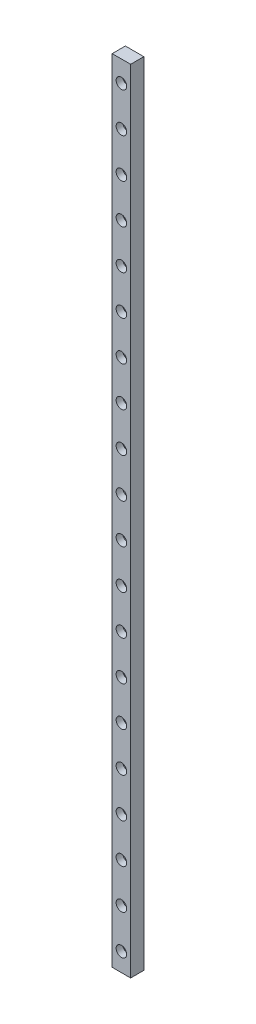
SolidWorks part; units mm, degrees
ref_plane "Front Plane" through (0, 0, 0) normal (0, 0, 1) x (1, 0, 0)
ref_plane "Top Plane" through (0, 0, 0) normal (0, 1, 0) x (1, 0, 0)
ref_plane "Right Plane" through (0, 0, 0) normal (1, 0, 0) x (0, 0, -1)
sketch "草图1" plane through (0, 0, 0) normal (0, 1, 0) x (1, 0, 0)
  line L1 (-3.5, 2.5) -> (3.5, 2.5)
  line L2 (-3.5, 2.5) -> (-3.5, -2.5)
  line L3 (-3.5, -2.5) -> (3.5, -2.5)
  line L4 (3.5, 2.5) -> (3.5, -2.5)
  line L5 (-3.5, 2.5) -> (3.5, -2.5) construction
  line L6 (-3.5, -2.5) -> (3.5, 2.5) construction
  point P0 (0, 0)
  dimension "D1" = 5
  dimension "D2" = 7
extrude "凸台-拉伸1" add sketch "草图1" along normal blind 300
sketch "草图2" plane through (0, 0, 2.5) normal (0, 0, 1) x (1, 0, 0)
  line L0 (-3.5, 0) -> (3.5, 0) construction
  circle A0 centre (0, 7) radius 1.25
  circle A1 centre (0, 22) radius 1.25
  circle A2 centre (0, 37) radius 1.25
  circle A3 centre (0, 52) radius 1.25
  circle A4 centre (0, 67) radius 1.25
  circle A5 centre (0, 82) radius 1.25
  circle A6 centre (0, 97) radius 1.25
  circle A7 centre (0, 112) radius 1.25
  circle A8 centre (0, 127) radius 1.25
  circle A9 centre (0, 142) radius 1.25
  circle A10 centre (0, 157) radius 1.25
  circle A11 centre (0, 172) radius 1.25
  circle A12 centre (0, 187) radius 1.25
  circle A13 centre (0, 202) radius 1.25
  circle A14 centre (0, 217) radius 1.25
  circle A15 centre (0, 232) radius 1.25
  circle A16 centre (0, 247) radius 1.25
  circle A17 centre (0, 262) radius 1.25
  circle A18 centre (0, 277) radius 1.25
  circle A19 centre (0, 292) radius 1.25
  dimension "D1" = 2.5
  dimension "D2" = 7
  dimension "D3" = 20
extrude "切除-拉伸1" cut sketch "草图2" against normal blind 300
sketch "草图3" plane through (0, 0, 2.5) normal (0, 0, 1) x (1, 0, 0)
  circle A0 centre (0, 7) radius 2
  circle A1 centre (0, 22) radius 2
  circle A2 centre (0, 37) radius 2
  circle A3 centre (0, 52) radius 2
  circle A4 centre (0, 67) radius 2
  circle A5 centre (0, 82) radius 2
  circle A6 centre (0, 97) radius 2
  circle A7 centre (0, 112) radius 2
  circle A8 centre (0, 127) radius 2
  circle A9 centre (0, 142) radius 2
  circle A10 centre (0, 157) radius 2
  circle A11 centre (0, 172) radius 2
  circle A12 centre (0, 187) radius 2
  circle A13 centre (0, 202) radius 2
  circle A14 centre (0, 217) radius 2
  circle A15 centre (0, 232) radius 2
  circle A16 centre (0, 247) radius 2
  circle A17 centre (0, 262) radius 2
  circle A18 centre (0, 277) radius 2
  circle A19 centre (0, 292) radius 2
  dimension "D1" = 4
  dimension "D2" = 20
extrude "切除-拉伸2" cut sketch "草图3" against normal blind 2.5
